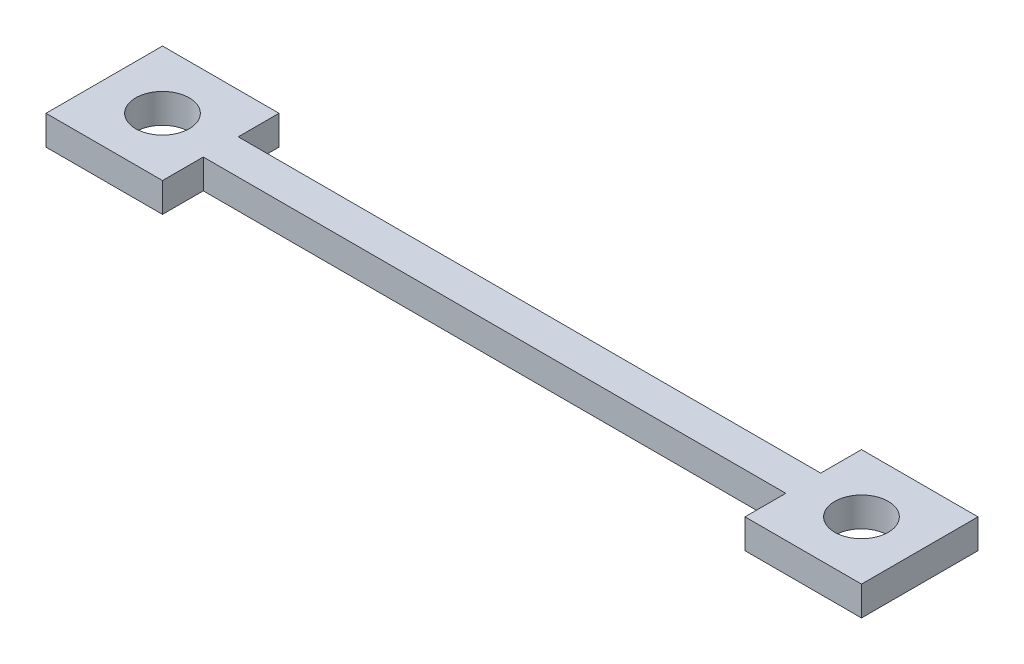
SolidWorks part; units mm, degrees
material "Commercially Pure CP-Ti UNS R50400 (SS)"
ref_plane "Front Plane" through (0, 0, 0) normal (0, 0, 1) x (1, 0, 0)
ref_plane "Top Plane" through (0, 0, 0) normal (0, 1, 0) x (1, 0, 0)
ref_plane "Right Plane" through (0, 0, 0) normal (1, 0, 0) x (0, 0, -1)
sketch "Sketch1" plane through (0, 0, 0) normal (0, 1, 0) x (1, 0, 0)
  line L0 (-41.424, -10.2833) -> (-41.424, -12.5058)
  line L1 (-47.774, -12.5058) -> (-41.424, -12.5058)
  line L2 (-47.774, -12.5058) -> (-47.774, -6.1558)
  line L3 (-47.774, -6.1558) -> (-41.424, -6.1558)
  line L4 (-3.324, -12.5058) -> (-3.324, -6.1558)
  line L7 (-41.424, -10.2833) -> (-9.674, -10.2833)
  line L9 (-41.424, -8.3783) -> (-9.674, -8.3783)
  line L13 (-41.424, -8.3783) -> (-41.424, -6.1558)
  line L14 (-9.674, -8.3783) -> (-9.674, -6.1558)
  line L15 (-9.674, -10.2833) -> (-9.674, -12.5058)
  line L16 (-9.674, -6.1558) -> (-3.324, -6.1558)
  line L17 (-9.674, -12.5058) -> (-3.324, -12.5058)
  point P0 (0, 0)
  point P6 (0, 0)
  dimension "D1" = 44.45
  dimension "D2" = 6.35
  dimension "D3" = 6.35
  dimension "D4" = 1.905
extrude "Boss-Extrude1" add sketch "Sketch1" along normal mid plane 1.6002
hole_wizard "#97 (0.0059) Diameter Hole1" positions "Sketch4" profile "Sketch3" hole size "#97" standard "Ansi Inch" end condition through all
sketch "Sketch4" plane through (0, 0.8001, 0) normal (0, 1, 0) x (-1, 0, 0)
  line L0 (47.774, 12.5058) -> (41.424, 6.1558) construction
  point P0 (44.599, 9.3308)
sketch "Sketch3" plane through (-44.599, 0.8001, 9.3308) normal (1, 0, 0) x (0, 0, 1)
  line L0 (0, 0) -> (0, 1.6002)
  line L1 (0, 1.6002) -> (1.4605, 1.6002)
  line L2 (1.4605, 1.6002) -> (1.4605, 0)
  line L5 (1.4605, 0) -> (0, 0)
  line L11 (0, -6.35) -> (0, 107.95) construction
  dimension "Thru Hole Dia." = 2.921
  dimension "Thru Hole Depth" = 1.6002
ref_plane "Plane1" through (-25.549, 0, 0) normal (1, 0, 0) x (0, 0, -1)
mirror "Mirror1" about plane through (-25.549, 0, 0) normal (1, 0, 0) of "#97 (0.0059) Diameter Hole1"
